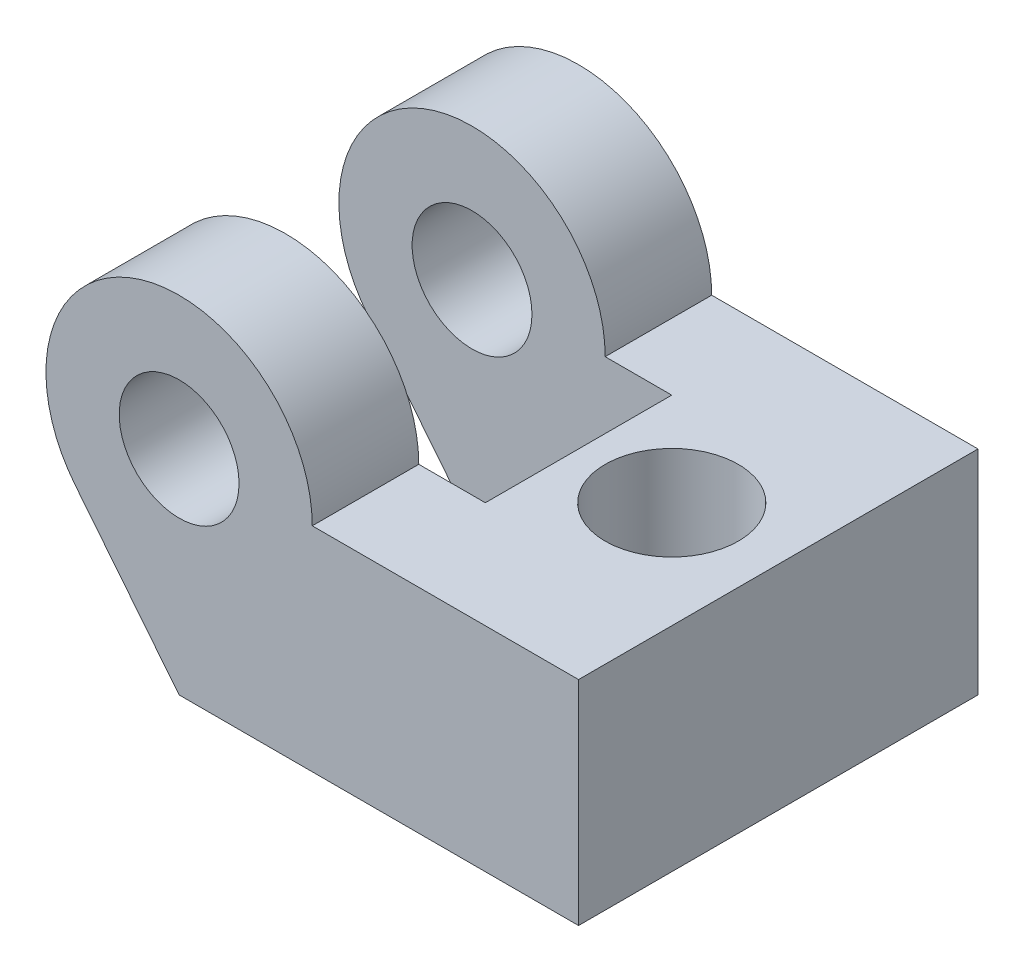
SolidWorks part; units mm, degrees
material "Printed PLA"
ref_plane "Front Plane" through (0, 0, 0) normal (0, 0, 1) x (1, 0, 0)
ref_plane "Top Plane" through (0, 0, 0) normal (0, 1, 0) x (1, 0, 0)
ref_plane "Right Plane" through (0, 0, 0) normal (1, 0, 0) x (0, 0, -1)
sketch "Sketch1" plane through (0, 0, 0) normal (0, 1, 0) x (1, 0, 0)
  line L1 (0, 7.5) -> (-15, 7.5)
  line L2 (0, 7.5) -> (0, -7.5)
  line L3 (0, -7.5) -> (-15, -7.5)
  line L4 (-15, 7.5) -> (-15, -7.5)
  dimension "D1" = 15
  dimension "D2" = 15
extrude "Boss-Extrude1" add sketch "Sketch1" along normal blind 8
sketch "Sketch2" plane through (0, 0, 7.5) normal (0, 0, 1) x (1, 0, 0)
  line L0 (-15, 0) -> (0, 0) construction
  line L1 (0, 8) -> (0, 0) construction
  line L2 (-18.9031, 4.875) -> (-15, 0)
  line L3 (-15, 0) -> (-15, 3)
  line L4 (-15, 8) -> (-15, 0) construction
  arc A0 (-15, 3) -> (-18.9031, 4.875) centre (-15, 8) ccw
  dimension "D1" = 10
  dimension "D3" = 15
  dimension "D2" = 8
extrude "Boss-Extrude2" add sketch "Sketch2" against normal offset from surface (4 mm away) 3.5 up to plane "Front Plane"
mirror "Mirror1" about plane through (0, 0, 0) normal (0, 0, 1) of "Boss-Extrude2"
sketch "Sketch3" plane through (0, 0, -3.5) normal (0, 0, 1) x (1, 0, 0)
  circle A0 centre (-15, 8) radius 7.5
  dimension "D1" = 15
extrude "Cut-Extrude1" cut sketch "Sketch3" along normal up to surface (7 mm away) up to face at (-15.2769, 6.7888, 3.5)
sketch "Sketch4" plane through (0, 0, 7.5) normal (0, 0, 1) x (1, 0, 0)
  circle A0 centre (-15, 8) radius 2.25
  dimension "D1" = 4.5
extrude "Cut-Extrude2" cut sketch "Sketch4" against normal through all
sketch "Sketch5" plane through (0, 8, 0) normal (0, 1, 0) x (1, 0, 0)
  line L0 (-4, 0) -> (0, 0) construction
  circle A0 centre (-4, 0) radius 2.5
  dimension "D1" = 5
  dimension "D2" = 4
extrude "Cut-Extrude3" cut sketch "Sketch5" against normal through all
